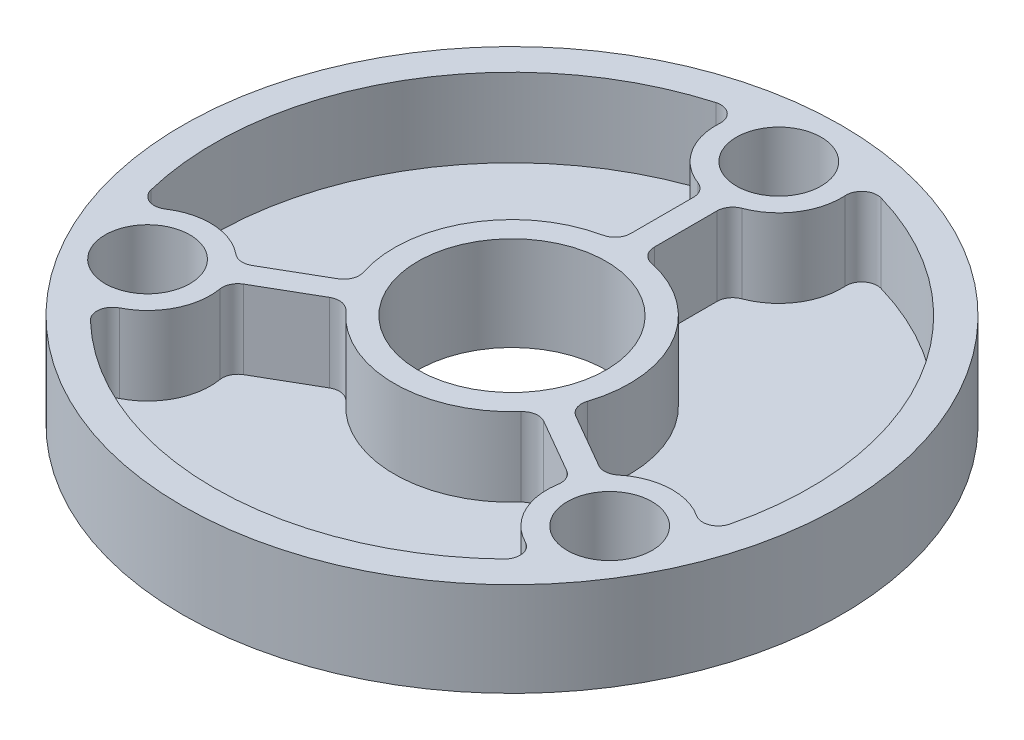
SolidWorks part; units mm, degrees
ref_plane "Front Plane" through (0, 0, 0) normal (0, 0, 1) x (1, 0, 0)
ref_plane "Top Plane" through (0, 0, 0) normal (0, 1, 0) x (1, 0, 0)
ref_plane "Right Plane" through (0, 0, 0) normal (1, 0, 0) x (0, 0, -1)
sketch "Sketch1" plane through (0, 0, 0) normal (0, 1, 0) x (1, 0, 0)
  circle A0 centre (0, 0) radius 21
  circle A1 centre (0, 0) radius 6
  dimension "D1" = 42
  dimension "D2" = 12
extrude "Boss-Extrude1" add sketch "Sketch1" along normal blind 1
sketch "Sketch2" plane through (0, 1, 0) normal (0, 1, 0) x (1, 0, 0)
  line L0 (0, 0) -> (0, 21) construction
  line L1 (-0.75, 12.3163) -> (-0.75, 8.3179)
  line L2 (0.75, 12.3163) -> (0.75, 8.3179)
  line L3 (10.2912, -6.8076) -> (6.8285, -4.8085)
  line L4 (11.0412, -5.5086) -> (7.5785, -3.5094)
  line L5 (-11.0412, -5.5086) -> (-7.5785, -3.5094)
  line L6 (-10.2912, -6.8076) -> (-6.8285, -4.8085)
  circle A0 centre (0, 0) radius 21
  arc A1 (-5.2686, 18.2549) -> (-18.4435, -4.5647) centre (0, 0) ccw
  circle A2 centre (0, 17) radius 2.7
  circle A3 centre (14.7224, -8.5) radius 2.7
  circle A4 centre (-14.7224, -8.5) radius 2.7
  circle A5 centre (0, 0) radius 17 construction
  arc A6 (18.4435, -4.5647) -> (5.2686, 18.2549) centre (0, 0) ccw
  arc A7 (-13.1749, -13.6902) -> (13.1749, -13.6902) centre (0, 0) ccw
  arc A8 (-3.9931, 17.2353) -> (-1.4, 13.253) centre (0, 17) ccw
  arc A9 (16.9227, -5.1595) -> (12.1774, -5.4141) centre (14.7224, -8.5) ccw
  arc A10 (-12.9297, -12.0758) -> (-10.7774, -7.8389) centre (-14.7224, -8.5) ccw
  circle A11 centre (0, 0) radius 6
  arc A12 (-5.584, -5.0069) -> (5.584, -5.0069) centre (0, 0) ccw
  arc A13 (1.4, 13.253) -> (3.9931, 17.2353) centre (0, 17) ccw
  circle A14 centre (0, 0) radius 6 construction
  arc A15 (10.7774, -7.8389) -> (12.9297, -12.0758) centre (14.7224, -8.5) ccw
  arc A16 (-12.1774, -5.4141) -> (-16.9227, -5.1595) centre (-14.7224, -8.5) ccw
  arc A17 (11.0412, -5.5086) -> (12.1774, -5.4141) centre (11.5412, -4.6426) ccw
  arc A18 (10.2912, -6.8076) -> (10.7774, -7.8389) centre (9.7912, -7.6737) cw
  arc A19 (-11.0412, -5.5086) -> (-12.1774, -5.4141) centre (-11.5412, -4.6426) cw
  arc A20 (-10.2912, -6.8076) -> (-10.7774, -7.8389) centre (-9.7912, -7.6737) ccw
  arc A21 (0.75, 12.3163) -> (1.4, 13.253) centre (1.75, 12.3163) cw
  arc A22 (-0.75, 12.3163) -> (-1.4, 13.253) centre (-1.75, 12.3163) ccw
  arc A23 (-1.5441, 7.3393) -> (-7.1281, -2.3324) centre (0, 0) ccw
  arc A24 (7.1281, -2.3324) -> (1.5441, 7.3393) centre (0, 0) ccw
  arc A25 (-7.5785, -3.5094) -> (-7.1281, -2.3324) centre (-8.0785, -2.6434) ccw
  arc A26 (-6.8285, -4.8085) -> (-5.584, -5.0069) centre (-6.3285, -5.6745) cw
  arc A27 (6.8285, -4.8085) -> (5.584, -5.0069) centre (6.3285, -5.6745) ccw
  arc A28 (7.5785, -3.5094) -> (7.1281, -2.3324) centre (8.0785, -2.6434) cw
  arc A29 (0.75, 8.3179) -> (1.5441, 7.3393) centre (1.75, 8.3179) ccw
  arc A30 (-0.75, 8.3179) -> (-1.5441, 7.3393) centre (-1.75, 8.3179) cw
  arc A31 (16.9227, -5.1595) -> (18.4435, -4.5647) centre (17.4728, -4.3244) ccw
  arc A32 (12.9297, -12.0758) -> (13.1749, -13.6902) centre (12.4815, -12.9697) cw
  arc A33 (-12.9297, -12.0758) -> (-13.1749, -13.6902) centre (-12.4815, -12.9697) ccw
  arc A34 (-16.9227, -5.1595) -> (-18.4435, -4.5647) centre (-17.4728, -4.3244) cw
  arc A35 (5.2686, 18.2549) -> (3.9931, 17.2353) centre (4.9913, 17.2941) ccw
  arc A36 (-5.2686, 18.2549) -> (-3.9931, 17.2353) centre (-4.9913, 17.2941) cw
  point P14 (0, 0)
  point P34 (0, 0)
  point P46 (0.75, 13.0709)
  point P49 (-0.75, 13.0709)
  point P59 (0.75, 7.4624)
  point P62 (-0.75, 7.4624)
  dimension "D1" = 38
  dimension "D2" = 42
  dimension "D3" = 5.4
  dimension "D6" = 8
  dimension "D7" = 15
  dimension "D10" = 1
  dimension "D11" = 1
  dimension "D12" = 1
  dimension "D4" = 17
  dimension "D8" = 1.5
  dimension "D5" = 3
  dimension "D9" = 3
extrude "Boss-Extrude2" add sketch "Sketch2" along normal blind 5
sketch "Sketch3" plane through (0, 1, 0) normal (0, 1, 0) x (1, 0, 0)
  circle A0 centre (-14.7224, -8.5) radius 1.3
  circle A1 centre (14.7224, -8.5) radius 1.3
  circle A2 centre (0, 17) radius 1.3
  dimension "D1" = 2.6
extrude "Cut-Extrude1" cut sketch "Sketch3" against normal blind 4
